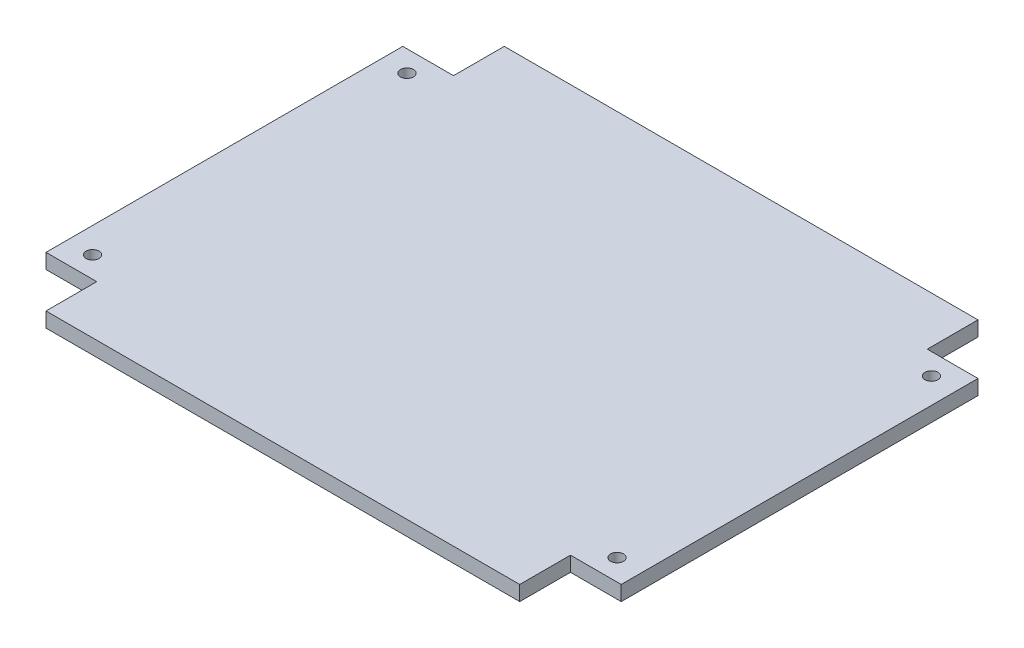
SolidWorks part; units mm, degrees
ref_plane "Front Plane" through (0, 0, 0) normal (0, 0, 1) x (1, 0, 0)
ref_plane "Top Plane" through (0, 0, 0) normal (0, 1, 0) x (1, 0, 0)
ref_plane "Right Plane" through (0, 0, 0) normal (1, 0, 0) x (0, 0, -1)
sketch "Sketch1" plane through (0, 0, 0) normal (0, 1, 0) x (1, 0, 0)
  line L1 (107.95, -86.0016) -> (-107.95, -86.0016)
  line L2 (107.95, -86.0016) -> (107.95, 86.0016)
  line L3 (107.95, 86.0016) -> (-107.95, 86.0016)
  line L4 (-107.95, -86.0016) -> (-107.95, 86.0016)
  line L5 (107.95, -86.0016) -> (-107.95, 86.0016) construction
  line L6 (107.95, 86.0016) -> (-107.95, -86.0016) construction
  point P0 (0, 0)
  dimension "D1" = 215.9
  dimension "D2" = 172.0032
extrude "Boss-Extrude1" add sketch "Sketch1" along normal blind 5.588
sketch "Sketch2" plane through (0, 5.588, 0) normal (0, 1, 0) x (1, 0, 0)
  line L0 (-107.95, 86.0016) -> (-107.95, -86.0016) construction
  line L1 (-107.95, 86.0016) -> (-88.9, 86.0016)
  line L2 (-107.95, 86.0016) -> (-107.95, 66.9516)
  line L3 (-107.95, 66.9516) -> (-88.9, 66.9516)
  line L4 (-88.9, 86.0016) -> (-88.9, 66.9516)
  line L5 (107.95, 86.0016) -> (88.9, 86.0016)
  line L6 (107.95, 86.0016) -> (107.95, 66.9516)
  line L7 (107.95, 66.9516) -> (88.9, 66.9516)
  line L8 (88.9, 86.0016) -> (88.9, 66.9516)
  line L9 (107.95, -86.0016) -> (88.9, -86.0016)
  line L10 (107.95, -86.0016) -> (107.95, -66.9516)
  line L11 (107.95, -66.9516) -> (88.9, -66.9516)
  line L12 (88.9, -86.0016) -> (88.9, -66.9516)
  line L13 (-107.95, -86.0016) -> (-88.9, -86.0016)
  line L14 (-107.95, -86.0016) -> (-107.95, -66.9516)
  line L15 (-107.95, -66.9516) -> (-88.9, -66.9516)
  line L16 (-88.9, -86.0016) -> (-88.9, -66.9516)
  line L17 (-107.95, -86.0016) -> (107.95, -86.0016) construction
  dimension "D1" = 19.05
extrude "CornerCut" cut sketch "Sketch2" against normal through all
sketch "Sketch3" plane through (0, 5.588, 0) normal (0, 1, 0) x (1, 0, 0)
  line L0 (-98.425, 66.9516) -> (-98.425, 59.0141) construction
  line L1 (-107.95, 66.9516) -> (-88.9, 66.9516) construction
  line L2 (-98.425, -66.9516) -> (-98.425, -59.0141) construction
  line L3 (-88.9, -66.9516) -> (-107.95, -66.9516) construction
  line L4 (98.425, -66.9516) -> (98.425, -59.0141) construction
  line L5 (107.95, -66.9516) -> (88.9, -66.9516) construction
  line L6 (98.425, 66.9516) -> (98.425, 59.0141) construction
  line L7 (88.9, 66.9516) -> (107.95, 66.9516) construction
  circle A0 centre (-98.425, 59.0141) radius 2.4257
  circle A1 centre (-98.425, -59.0141) radius 2.4257
  circle A2 centre (98.425, -59.0141) radius 2.4257
  circle A3 centre (98.425, 59.0141) radius 2.4257
  dimension "D2" = 4.8514
  dimension "D1" = 7.9375
extrude "MountHoles" cut sketch "Sketch3" against normal through all
equation "\"Height\"= 32in"
equation "\"Width\"= 23in"
equation "\"Depth\"= 20in"
equation "\"Plexi\"= .121in"
equation "\"MagnetThickness\"=3mm"
equation "\"MagnetDiameter\"=12mm"
equation "\"DoorPlexi\"= \"Plexi\""
equation "\"BasePlateThickness\"= 0.5in"
equation "\"BasePlateWidth\"= \"Width\"+\"EBWidth\"-2*\"Plexi\""
equation "\"BasePlateDepth\"= \"Depth\"-\"Plexi\"-\"DoorPlexi\""
equation "\"Boxsize\"= .75in"
equation "\"BoxsizeHalf\"= \"Boxsize\"/2"
equation "\"Boxinner\"= .625in"
equation "\"CornerCube\"= 0.75in"
equation "\"FingerLength\"= 1.125in"
equation "\"FingerWidth\"= .625in"
equation "\"Cutwidth\"= .016in"
equation "\"Earsize\"= 1in + \"Cutwidth\" /2"
equation "\"Slotsize\"= 1in - \"Cutwidth\" / 2"
equation "\"InnerWidth\"= \"Width\" - 2* \"Plexi\""
equation "\"InnerHeight\"= \"Height\" -2 * \"Plexi\""
equation "\"InnerDepth\"= \"Depth\" - 2*\"Plexi\""
equation "\"RearNumHoles\"= 7"
equation "\"RearHolesBorder\"= 2.2"
equation "\"RearHoleSpacing\"= (\"Width\" - 2*\"RearHolesBorder\") / (\"RearNumHoles\"-1)"
equation "\"RearBarLength\"= (\"InnerWidth\"-2*\"CornerCube\")"
equation "\"RearTopNumHoles\"= 6"
equation "\"RearTopHolesBorder\"= 2.5"
equation "\"RearTopHolesSpacing\"= (\"Width\" - 2*\"RearTopHolesBorder\") / (\"RearTopNumHoles\"-1)"
equation "\"SideTopNumHoles\"= 5"
equation "\"SideTopHoleOffset\"=\"CornerCube\"+\"FingerLength\"+\"Plexi\"+.5"
equation "\"SideHorizNumHoles\"= 6"
equation "\"SideHorizHoleBorder\"= 2.25"
equation "\"SideVertBarLength\"=\"Height\"-\"BasePlateThickness\"-2*\"CornerCube\"-\"Plexi\""
equation "\"SideVertNumHoles\"= 6"
equation "\"SideVertHolesBorder\"= \"CornerCube\"+\"FingerLength\"+.9"
equation "\"SideVertHoleSpacing\"= (\"InnerHeight\" - 2*\"SideVertHolesBorder\") / (\"SideVertNumHoles\"-1)"
equation "\"RearSideVertNumHoles\"= 7"
equation "\"RearSideVertHolesBorder\"= 2.5"
equation "\"RearSideVertHoleSpacing\"= (\"InnerHeight\" - 2*\"RearSideVertHolesBorder\") / (\"RearSideVertNumHoles\"-1)"
equation "\"RivetDia\"= .228in"
equation "\"SlotDepth\"= \"Plexi\" + 0.75in + .005in"
equation "\"SideSlotWidth\"= \"Plexi\"+.005in"
equation "\"SidePanelVertSpacing\"= (\"Height\"-2*(1.75-\"Plexi\")) / 5"
equation "\"BottomPanelSideHoleSpacing\"= (\"InnerDepth\"-2*(1.75-\"Plexi\")) / 4"
equation "\"FrontDoorGap\"= .1in"
equation "\"TopDepth\"= \"Depth\"-\"DoorPlexi\"-\"FrontDoorGap\""
equation "\"TopBarDepth\"= \"Depth\"-\"DoorPlexi\"-\"Plexi\"-2*\"MagnetThickness\"-2*\"CornerCube\""
equation "\"CoolerDepth\"= 12in"
equation "\"ShelfDepth\"= \"TopBarDepth\"+\"CornerCube\"-\"CoolerDepth\""
equation "\"ShelfBarWidth\"= \"EBWidth\"-\"Boxsize\""
equation "\"ShelfGap\"= 0.5in"
equation "\"ShelfBarWidthShort\"= \"ShelfBarWidth\"-\"Boxsize\"-\"ShelfGap\""
equation "\"IntakeWidth\"=4in"
equation "\"IntakeHeight\"=2in"
equation "\"ExhaustWidth\"=4in"
equation "\"ExhaustHeight\"=2in"
equation "\"VentSpacing\"=7in"
equation "\"AngleBracketLength\"=20mm"
equation "\"AngleBracketWidth\"=.5in"
equation "\"AngleBracketThickness\"=.125in"
equation "\"AngleBracketHolePos\"=15mm"
equation "\"AngleBracketHoleDia\"=\"Rivet3_16Dia\""
equation "\"ShelfBarAngleHole\"=\"ShelfGap\"+\"Boxsize\"+\"AngleBracketHolePosShort\""
equation "\"SideTopHoleSpacing\"= (\"TopBarDepth\"-2*\"SideTopHoleOffset\") / (\"SideTopNumHoles\"-1)"
equation "\"SideHorizHoleSpacing\"= (\"TopBarDepth\"-2*\"SideHorizHoleBorder\") / (\"SideHorizNumHoles\"-1)"
equation "\"ShelfWidth\"= \"EBWidth\"-\"ShelfGap\""
equation "\"D1@Sketch1\"=\"ShelfWidth\""
equation "\"D2@Sketch1\"=\"ShelfDepth\""
equation "\"D1@Boss-Extrude1\"=\"ShelfThickness\""
equation "\"D1@Sketch2\"=\"Boxsize\""
equation "\"D1@Sketch3\"=\"AngleBracketHolePosShort\""
equation "\"D2@Sketch3\"=\"Rivet3_16Dia\""
equation "\"EBWidth\"= 9in"
equation "\"ShelfBarDepth\"=\"ShelfDepth\"-2*\"CornerCube\""
equation "\"ComponentMountDia\"=0.1770"
equation "\"ShelfThickness\"= .220in"
equation "\"ShelfHeight1\"= 13in"
equation "\"ShelfHeight2\"= 24in"
equation "\"VentVertLocation\"=12.75in"
equation "\"Rivet3_16Dia\"= .191in"
equation "\"BinderPostDia\"= .228in"
equation "\"PSBracketThickness\"= .0641in"
equation "\"EBForwardMountOffset\"= 4.0in"
equation "\"EBForwardMount\"= 2*\"Boxsize\"+\"CoolerDepth\"+\"EBForwardMountOffset\""
equation "\"EBRearwardMountOffset\"= 1.5in"
equation "\"EBRearwardMount\"= \"Boxsize\"+\"EBRearwardMountOffset\""
equation "\"AngleBracketLengthShort\"=.625in"
equation "\"AngleBracketLengthLong\"=1in"
equation "\"AngleBracketHolePosShort\"=.3125in"
equation "\"AngleBracketHolePosLong\"=.640625in"
